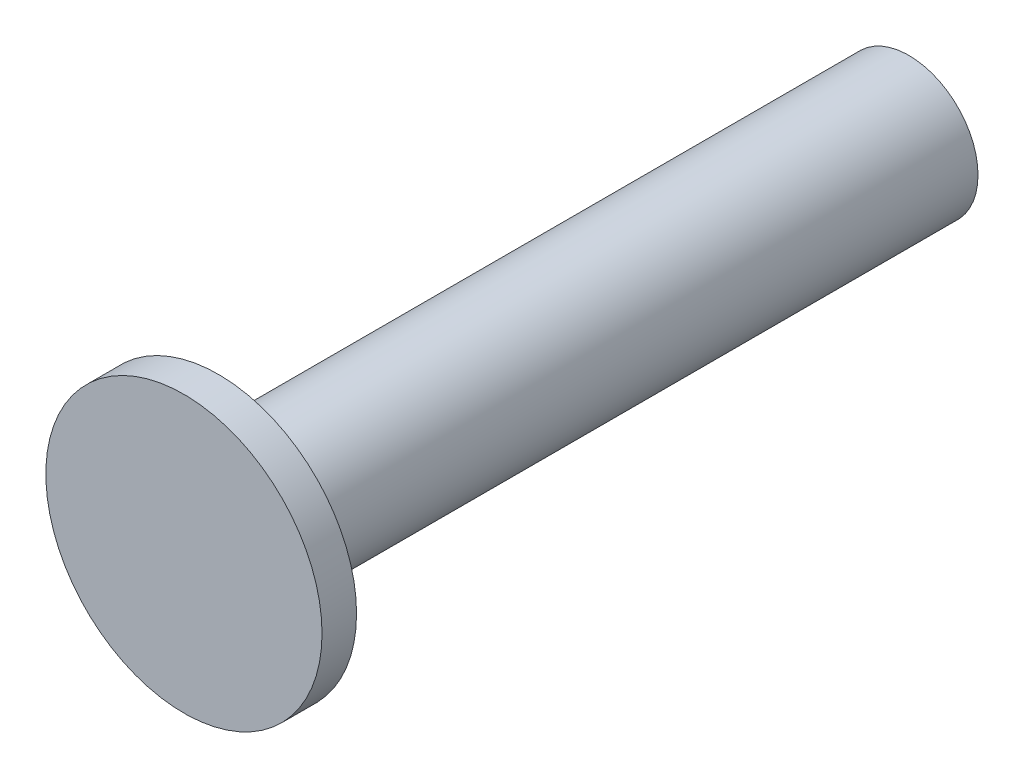
SolidWorks part; units mm, degrees
material "1023 Carbon Steel Sheet (SS)"
ref_plane "Front Plane" through (0, 0, 0) normal (0, 0, 1) x (1, 0, 0)
ref_plane "Top Plane" through (0, 0, 0) normal (0, 1, 0) x (1, 0, 0)
ref_plane "Right Plane" through (0, 0, 0) normal (1, 0, 0) x (0, 0, -1)
sketch "Sketch1" plane through (0, 0, 0) normal (0, 0, 1) x (1, 0, 0)
  circle A0 centre (0, 0) radius 2
extrude "Boss-Extrude1" add sketch "Sketch1" along normal blind 20
sketch "Sketch2" plane through (0, 0, 20) normal (0, 0, 1) x (1, 0, 0)
  circle A0 centre (0, 0) radius 4
extrude "Boss-Extrude2" add sketch "Sketch2" along normal blind 1
